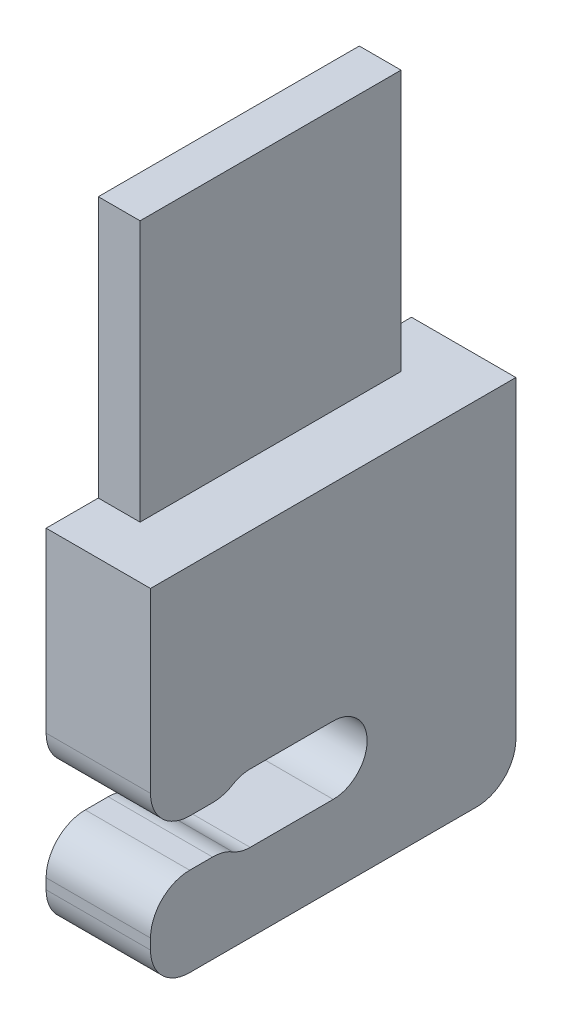
SolidWorks part; units mm, degrees
ref_plane "Front Plane" through (0, 0, 0) normal (0, 0, 1) x (1, 0, 0)
ref_plane "Top Plane" through (0, 0, 0) normal (0, 1, 0) x (1, 0, 0)
ref_plane "Right Plane" through (0, 0, 0) normal (1, 0, 0) x (0, 0, -1)
sketch "Sketch1" plane through (0, 0, 0) normal (1, 0, 0) x (0, 0, -1)
  line L1 (0, 0) -> (10, 0)
  line L2 (0, 0) -> (0, -10)
  line L3 (0, -10) -> (10, -10)
  line L4 (10, 0) -> (10, -10)
  dimension "D1" = 10
  dimension "D2" = 10
extrude "Boss-Extrude1" add sketch "Sketch1" along normal blind 1.6
sketch "Sketch2" plane through (0, 0, 0) normal (0, 0, 1) x (1, 0, 0)
  line L3 (1.2, -12) -> (0, -12)
  line L4 (0, -10) -> (0, -12)
  line L5 (1.6, -10) -> (4, -10)
  line L7 (2.8, -12) -> (4, -12)
  line L8 (4, -10) -> (4, -12)
  line L9 (1.2, -12) -> (2.8, -12)
  line L11 (0, -10) -> (1.6, -10)
  point P10 (0, 0)
  line M8 (0, -10) -> (1.6, -10)
  dimension "D1" = 4
  dimension "D2" = 2
  dimension "D3" = 0
extrude "Boss-Extrude2" add sketch "Sketch2" against normal up to surface (10 mm away) contours L3 L9 L7 L8 L5 L4 M8 up to face at (0.8, -5, -10)
sketch "Sketch3" plane through (0, 0, 0) normal (0, 0, 1) x (1, 0, 0)
  line L9 (4, -10) -> (0, -10)
  line L10 (4, -10) -> (4, -12)
  line L11 (4, -12) -> (0, -12)
  line L12 (0, -10) -> (0, -12)
extrude "Boss-Extrude3" add sketch "Sketch3" along normal blind 2
sketch "Sketch4" plane through (0, 0, -10) normal (0, 0, -1) x (-1, 0, 0)
  line L0 (-4, -10) -> (-1.6, -10) construction
  line L5 (-4, -10) -> (0, -10)
  line L6 (-4, -10) -> (-4, -12)
  line L7 (-4, -12) -> (0, -12)
  line L8 (0, -10) -> (0, -12)
  line L9 (-4, -12) -> (-4, -10) construction
  line L10 (0, -12) -> (-4, -12) construction
  line L11 (0, -12) -> (0, 0) construction
extrude "Boss-Extrude4" add sketch "Sketch4" along normal blind 2
sketch "Sketch5" plane through (4, 0, 0) normal (1, 0, 0) x (0, 0, -1)
  line L0 (12, -10) -> (12, -12) construction
  line L1 (-2, -12) -> (12, -12)
  line L2 (-2, -12) -> (-2, -22)
  line L3 (-0.5, -23.5) -> (10.5, -23.5)
  line L4 (12, -12) -> (12, -22)
  line L6 (5, -17.9) -> (-1.9684, -17.9)
  line L8 (8.7871, -20.5) -> (1.8187, -20.5)
  line L11 (1.8187, -18.3) -> (-2, -18.3)
  line L12 (-2, -16.6655) -> (-2, -18.3)
  line L15 (1.8187, -20.1) -> (-2, -20.1)
  line L16 (-2, -16.6655) -> (-2, -20.1)
  circle A0 centre (5, -19.2) radius 1.3
  circle A1 centre (1.8187, -19.2) radius 1.3
  arc A2 (10.5, -23.5) -> (12, -22) centre (10.5, -22) ccw
  arc A3 (-2, -22) -> (-0.5, -23.5) centre (-0.5, -22) ccw
  point P22 (12, -23.5)
  line M5 (-2, -12) -> (12, -12)
  dimension "D2" = 2.6
  dimension "D3" = 2.6
  dimension "D7" = 1.5
  dimension "D1" = 11.5
  dimension "D4" = 0.9
  dimension "D5" = 0.9
  dimension "D6" = 4.3
  dimension "D8" = 3.8187
  dimension "D9" = 7
extrude "Boss-Extrude5" add sketch "Sketch5" against normal up to surface (4 mm away) contours L2 A3 L3 A2 L4 L11 A1 L6 A0 L8 L15 M5 up to face at (0, -8, -5)
fillet "Fillet1" radius 1.5 4 edges at (2, -18.3, -0.8807) (2, -18.3, 2) (2, -20.1, 2) (2, -20.1, -0.8807)
